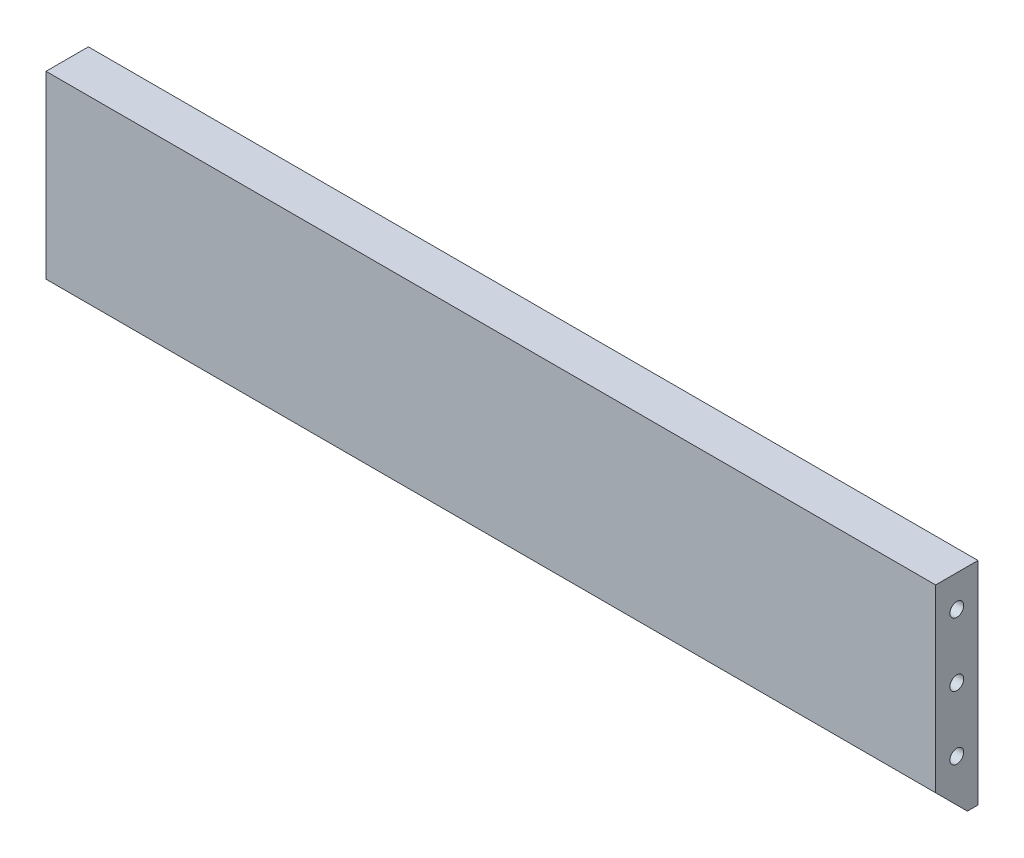
SolidWorks part; units mm, degrees
ref_plane "Ön Düzlem" through (0, 0, 0) normal (0, 0, 1) x (1, 0, 0)
ref_plane "Üst Düzlem" through (0, 0, 0) normal (0, 1, 0) x (1, 0, 0)
ref_plane "Sağ Düzlem" through (0, 0, 0) normal (1, 0, 0) x (0, 0, -1)
sketch "Çizim1" plane through (0, 0, 0) normal (0, 0, 1) x (1, 0, 0)
  line L1 (-210, 50) -> (210, 50)
  line L2 (-210, 50) -> (-210, -50)
  line L3 (-210, -50) -> (210, -50)
  line L4 (210, 50) -> (210, -50)
  line L5 (-210, 50) -> (210, -50) construction
  line L6 (-210, -50) -> (210, 50) construction
  point P0 (0, 0)
  dimension "D1" = 420
  dimension "D2" = 100
extrude "Yükseklik-Ekstrüzyon1" add sketch "Çizim1" along normal blind 20
chamfer "Pah1" distance 15 angle 45 1 edges at (0, -50, 20)
sketch "Çizim2" plane through (210, 0, 0) normal (1, 0, 0) x (0, 0, -1)
  line L0 (-20, 50) -> (0, 50) construction
  line L1 (-20, -35) -> (-20, 50) construction
  circle A0 centre (-10, 35) radius 3.25
  circle A1 centre (-10, 5) radius 3.25
  circle A2 centre (-10, -25) radius 3.25
  dimension "D1" = 6.5
  dimension "D2" = 15
  dimension "D3" = 30
  dimension "D4" = 30
  dimension "D5" = 10
extrude "Kes-Ekstrüzyon1" cut sketch "Çizim2" against normal blind 30
cosmetic thread "Kozmetik Diş Açma1" parameters "D2"=8
cosmetic thread "Kozmetik Diş Açma2" parameters "D2"=8
cosmetic thread "Kozmetik Diş Açma3" parameters "D2"=8
mirror "Aynalama1" about plane through (0, 0, 0) normal (1, 0, 0) of "Kes-Ekstrüzyon1"
cosmetic thread "Kozmetik Diş Açma4" parameters "D2"=8
cosmetic thread "Kozmetik Diş Açma5" parameters "D2"=8
cosmetic thread "Kozmetik Diş Açma6" parameters "D2"=8
